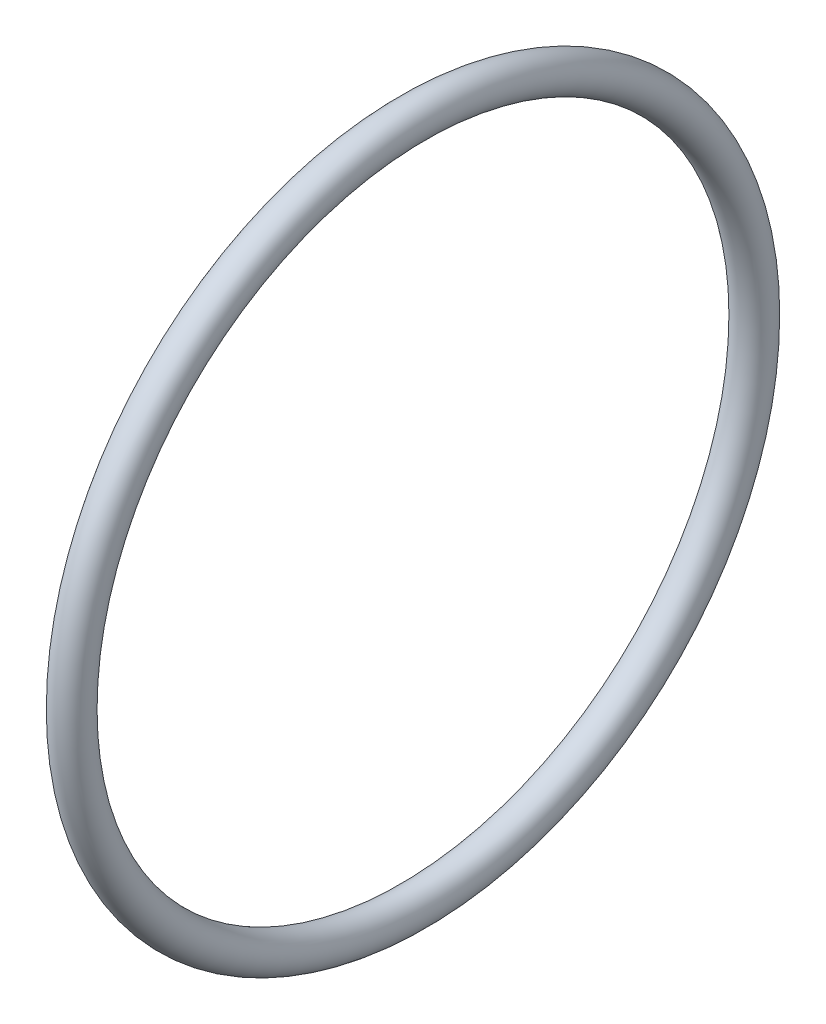
SolidWorks part; units mm, degrees
ref_plane "Front Plane" through (0, 0, 0) normal (0, 0, 1) x (1, 0, 0)
ref_plane "Top Plane" through (0, 0, 0) normal (0, 1, 0) x (1, 0, 0)
ref_plane "Right Plane" through (0, 0, 0) normal (1, 0, 0) x (0, 0, -1)
sketch "Sketch1" plane through (0, 0, 0) normal (0, 0, 1) x (1, 0, 0)
  line L0 (0, -2.5) -> (0, -47.5) construction
  line L1 (-2.6651, -47.5) -> (3.5672, -47.5) construction
  circle A0 centre (0, 0) radius 2.5
  dimension "D1" = 5
  dimension "D2" = 45
revolve "Revolve1" add sketch "Sketch1" angle 360 about L1
sketch "Sketch6" plane through (0, 0, 0) normal (0, 1, 0) x (1, 0, 0)
  line L0 (-2.5, 47.5) -> (-2.5, -47.5) construction
  line L1 (2.5, -47.5) -> (2.5, 47.5) construction
  line L2 (-2.5, 47.5) -> (-2.5, -47.5) construction
  line L3 (2.5, -47.5) -> (2.5, 47.5) construction
sketch "Sketch8" plane through (0, 0, 0) normal (1, 0, 0) x (0, 0, -1)
  circle A0 centre (0, -47.5) radius 50 construction
  circle A1 centre (0, -47.5) radius 45 construction
  circle A2 centre (0, -47.5) radius 50 construction
  circle A3 centre (0, -47.5) radius 45 construction
sketch "Sketch9" plane through (0, 0, 0) normal (1, 0, 0) x (0, 0, -1)
  circle A0 centre (0, -47.5) radius 20.1445
